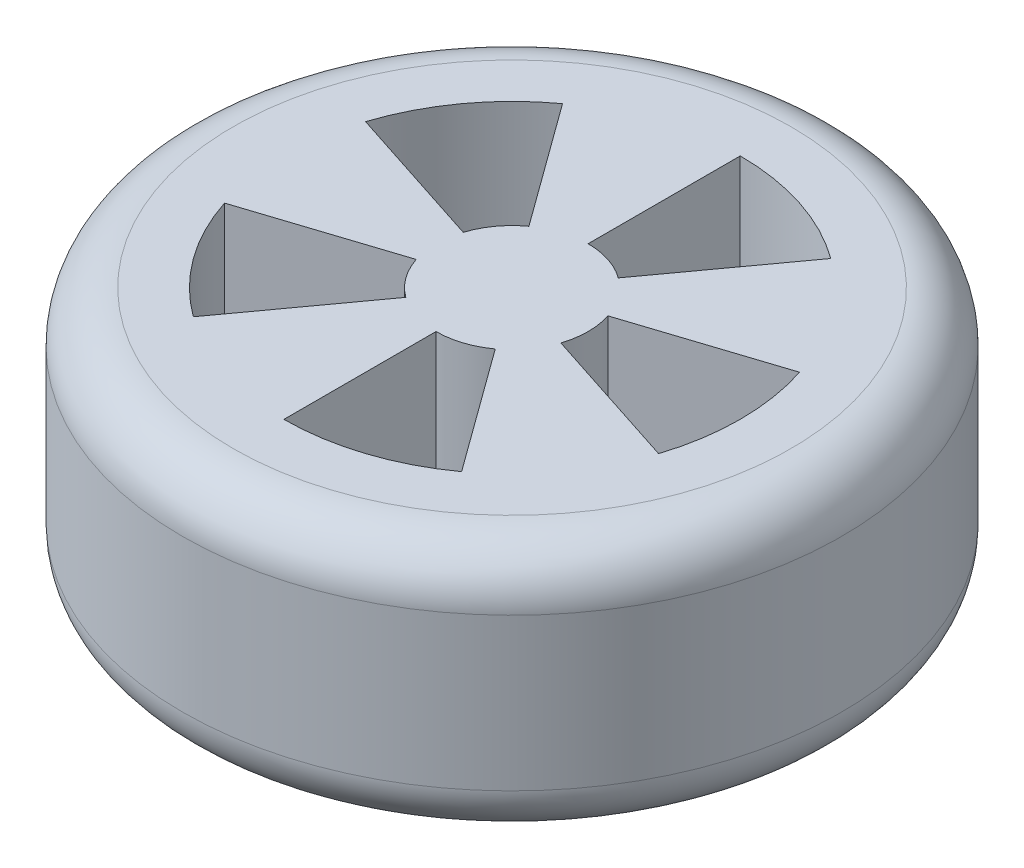
SolidWorks part; units mm, degrees
ref_plane "前视基准面" through (0, 0, 0) normal (0, 0, 1) x (1, 0, 0)
ref_plane "上视基准面" through (0, 0, 0) normal (0, 1, 0) x (1, 0, 0)
ref_plane "右视基准面" through (0, 0, 0) normal (1, 0, 0) x (0, 0, -1)
other "Configuration Table"
sketch "草图1" plane through (0, 0, 0) normal (0, 1, 0) x (1, 0, 0)
  line L0 (0, 7.5) -> (0, 22.5)
  line L1 (4.4084, 6.0676) -> (13.2252, 18.2029)
  line L2 (7.1329, 2.3176) -> (21.3988, 6.9529)
  line L3 (7.1329, -2.3176) -> (21.3988, -6.9529)
  line L4 (4.4084, -6.0676) -> (13.2252, -18.2029)
  line L5 (0, -7.5) -> (0, -22.5)
  line L6 (-4.4084, -6.0676) -> (-13.2252, -18.2029)
  line L7 (-7.1329, -2.3176) -> (-21.3988, -6.9529)
  line L8 (-7.1329, 2.3176) -> (-21.3988, 6.9529)
  line L9 (-4.4084, 6.0676) -> (-13.2252, 18.2029)
  circle A0 centre (0, 0) radius 32.5
  arc A1 (-13.2252, 18.2029) -> (-21.3988, 6.9529) centre (0, 0) ccw
  arc A2 (-4.4084, 6.0676) -> (-7.1329, 2.3176) centre (0, 0) ccw
  arc A3 (-21.3988, -6.9529) -> (-13.2252, -18.2029) centre (0, 0) ccw
  arc A4 (-7.1329, -2.3176) -> (-4.4084, -6.0676) centre (0, 0) ccw
  arc A5 (0, -7.5) -> (4.4084, -6.0676) centre (0, 0) ccw
  arc A6 (0, -22.5) -> (13.2252, -18.2029) centre (0, 0) ccw
  arc A7 (7.1329, -2.3176) -> (7.1329, 2.3176) centre (0, 0) ccw
  arc A8 (21.3988, -6.9529) -> (21.3988, 6.9529) centre (0, 0) ccw
  arc A9 (4.4084, 6.0676) -> (0, 7.5) centre (0, 0) ccw
  arc A10 (13.2252, 18.2029) -> (0, 22.5) centre (0, 0) ccw
  point P28 (0, 0)
  dimension "D1" = 65
  dimension "D2" = 10
  dimension "D3" = 15
  dimension "D4" = 10
extrude "凸台-拉伸1" add sketch "草图1" along normal blind 25
fillet "圆角1" radius 5 1 edges at (0, 25, 32.5)
fillet "圆角2" radius 5 1 edges at (0, 0, 32.5)
